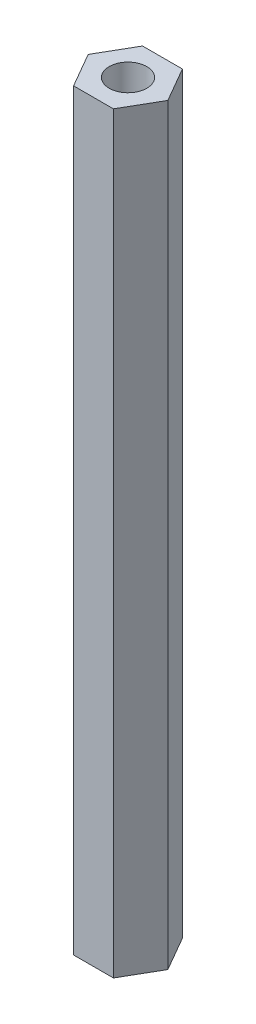
SolidWorks part; units mm, degrees
ref_plane "Front Plane" through (0, 0, 0) normal (0, 0, 1) x (1, 0, 0)
ref_plane "Top Plane" through (0, 0, 0) normal (0, 1, 0) x (1, 0, 0)
ref_plane "Right Plane" through (0, 0, 0) normal (1, 0, 0) x (0, 0, -1)
sketch "Sketch1" plane through (0, 0, 0) normal (0, 1, 0) x (1, 0, 0)
  line L1 (3.1754, 0) -> (1.5877, 2.75)
  line L2 (1.5877, 2.75) -> (-1.5877, 2.75)
  line L3 (-1.5877, 2.75) -> (-3.1754, 0)
  line L4 (-3.1754, 0) -> (-1.5877, -2.75)
  line L5 (-1.5877, -2.75) -> (1.5877, -2.75)
  line L6 (1.5877, -2.75) -> (3.1754, 0)
  circle A0 centre (0, 0) radius 2.75 construction
  dimension "D1" = 5.5
extrude "Boss-Extrude1" add sketch "Sketch1" along normal blind 60
sketch "Sketch2" plane through (0, 60, 0) normal (0, 1, 0) x (1, 0, 0)
  circle A0 centre (0, 0) radius 1.5
  dimension "D1" = 3
extrude "Cut-Extrude1" cut sketch "Sketch2" against normal blind 10
ref_plane "Plane1" through (0, 30, 0) normal (0, -1, 0) x (-1, 0, 0)
mirror "Mirror1" about plane through (0, 30, 0) normal (0, -1, 0) of "Cut-Extrude1"
